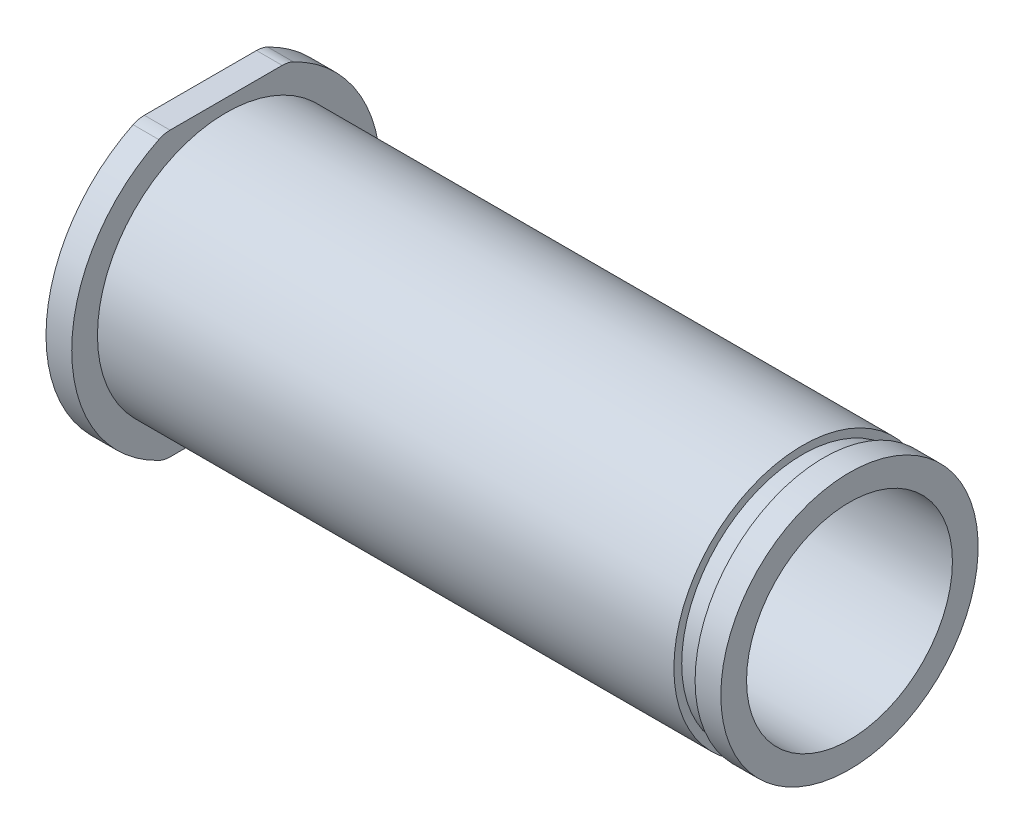
SolidWorks part; units mm, degrees
material "6061 Alloy"
ref_plane "Front Plane" through (0, 0, 0) normal (0, 0, 1) x (1, 0, 0)
ref_plane "Top Plane" through (0, 0, 0) normal (0, 1, 0) x (1, 0, 0)
ref_plane "Right Plane" through (0, 0, 0) normal (1, 0, 0) x (0, 0, -1)
sketch "Sketch1" plane through (0, 0, 0) normal (0, 0, 1) x (1, 0, 0)
  line L0 (0, 0) -> (80.0862, 0) construction
  line L1 (0, 19.05) -> (0, 12.7)
  line L2 (0, 12.7) -> (80.0862, 12.7)
  line L3 (80.0862, 12.7) -> (80.0862, 15.875)
  line L4 (80.0862, 15.875) -> (76.9112, 15.875)
  line L5 (76.9112, 15.875) -> (76.9112, 14.9098)
  line L6 (76.9112, 14.9098) -> (74.295, 14.9098)
  line L7 (74.295, 14.9098) -> (74.295, 15.875)
  line L8 (74.295, 15.875) -> (3.175, 15.875)
  line L9 (3.175, 15.875) -> (3.175, 19.05)
  line L10 (3.175, 19.05) -> (0, 19.05)
  dimension "D1" = 3.175
  dimension "D2" = 3.175
  dimension "D3" = 31.75
  dimension "D4" = 29.8196
  dimension "D5" = 2.6162
  dimension "D6" = 38.1
  dimension "D7" = 25.4
  dimension "D8" = 71.12
revolve "Revolve1" add sketch "Sketch1" angle 360 about L0
sketch "Sketch2" plane through (0, 0, 0) normal (-1, 0, 0) x (0, 0, 1)
  line L0 (0, 17.4625) -> (0, -17.4625) construction
  line L1 (-7.6134, 17.4625) -> (7.6134, 17.4625)
  line L2 (-7.6134, 17.4625) -> (-7.6134, 19.05)
  line L3 (-7.6134, 19.05) -> (7.6134, 19.05)
  line L4 (7.6134, 17.4625) -> (7.6134, 19.05)
  line L6 (-7.6134, -17.4625) -> (7.6134, -17.4625)
  line L7 (-7.6134, -17.4625) -> (-7.6134, -19.05)
  line L8 (-7.6134, -19.05) -> (7.6134, -19.05)
  line L9 (7.6134, -17.4625) -> (7.6134, -19.05)
  circle A0 centre (0, 0) radius 19.05 construction
  dimension "D1" = 38.1
  dimension "D2" = 34.925
extrude "Cut-Extrude1" cut sketch "Sketch2" against normal through all
fillet "Fillet1" radius 3.175 4 edges at (1.5875, -17.4625, 7.6134) (1.5875, -17.4625, -7.6134) (1.5875, 17.4625, -7.6134) (1.5875, 17.4625, 7.6134)
